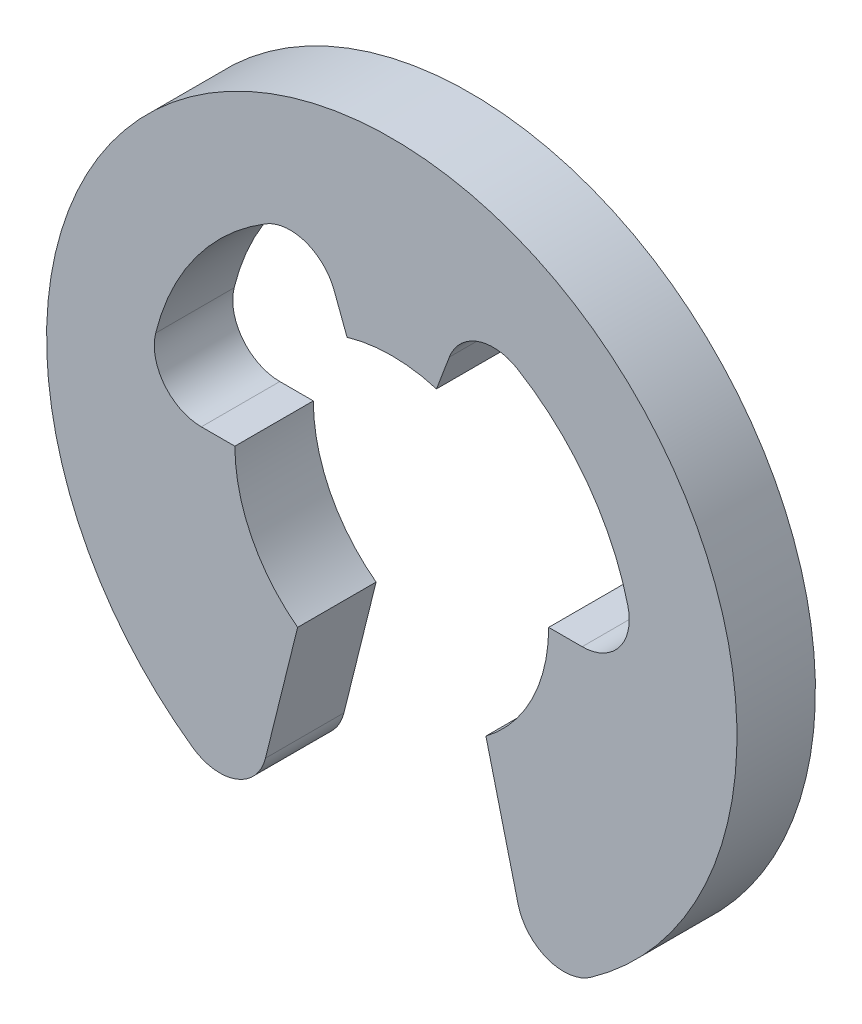
SolidWorks part; units mm, degrees
material "Plain Carbon Steel"
ref_plane "Front Plane" through (0, 0, 0) normal (0, 0, 1) x (1, 0, 0)
ref_plane "Top Plane" through (0, 0, 0) normal (0, 1, 0) x (1, 0, 0)
ref_plane "Right Plane" through (0, 0, 0) normal (1, 0, 0) x (0, 0, -1)
sketch "Sketch2" plane through (0, 0, 0) normal (0, 0, 1) x (1, 0, 0)
  line L0 (0.6, -0.8) -> (0.8999, -2.0075)
  line L1 (-0.6, -0.8) -> (-0.8999, -2.0075)
  line L2 (1, 0) -> (1.55, 0)
  line L3 (-1, 0) -> (-1.55, 0)
  line L4 (-0.4797, 1.4739) -> (-0.285, 0.9585)
  line L5 (0.4797, 1.4739) -> (0.285, 0.9585)
  arc A0 (0.8999, -2.0075) -> (-0.8999, -2.0075) centre (0, 0) ccw
  arc A1 (0.6, -0.8) -> (1, 0) centre (0, 0) ccw
  arc A2 (1.55, 0) -> (0.4797, 1.4739) centre (0, 0) ccw
  arc A3 (-1, 0) -> (-0.6, -0.8) centre (0, 0) ccw
  arc A4 (0.285, 0.9585) -> (-0.285, 0.9585) centre (0, 0) ccw
  arc A5 (-0.4797, 1.4739) -> (-1.55, 0) centre (0, 0) ccw
  dimension "D1" = 4.4
  dimension "D2" = 2
  dimension "D5" = 3.1
  dimension "D3" = 27.9
  dimension "D4" = 1.2
  dimension "D6" = 0.57
  dimension "D7" = 41.4
extrude "Boss-Extrude1" add sketch "Sketch2" along normal blind 0.5
fillet "Fillet1" radius 0.3 6 edges at (1.55, 0, 0.25) (-0.4797, 1.4739, 0.25) (0.4797, 1.4739, 0.25) (-0.8999, -2.0075, 0.25) (0.8999, -2.0075, 0.25) (-1.55, 0, 0.25)
